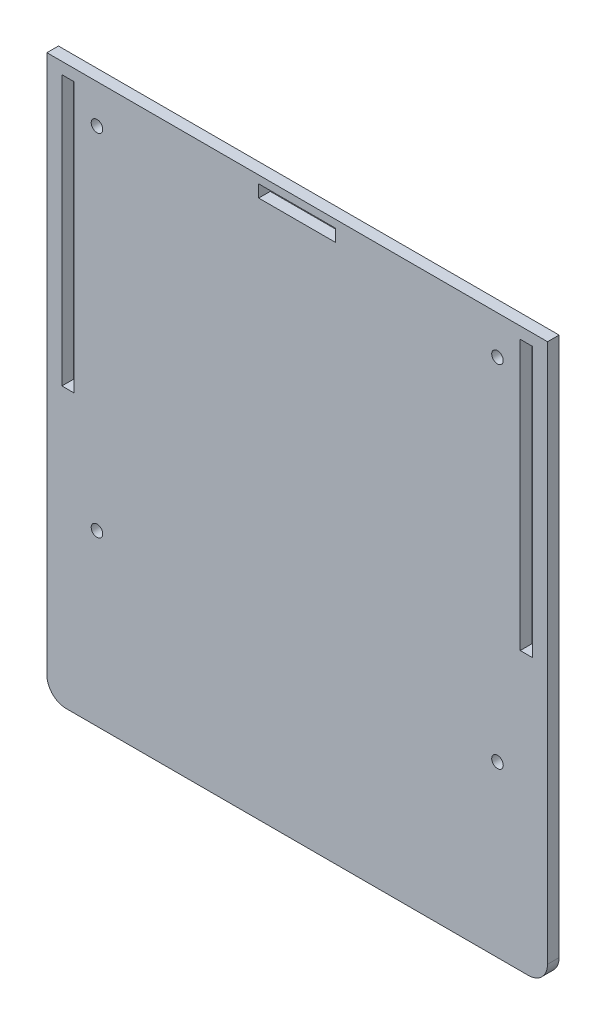
SolidWorks part; units mm, degrees
material "Maple"
ref_plane "Front Plane" through (0, 0, 0) normal (0, 0, 1) x (1, 0, 0)
ref_plane "Top Plane" through (0, 0, 0) normal (0, 1, 0) x (1, 0, 0)
ref_plane "Right Plane" through (0, 0, 0) normal (1, 0, 0) x (0, 0, -1)
sketch "Sketch1" plane through (0, 0, 0) normal (0, 0, 1) x (1, 0, 0)
  line L1 (-60, -75) -> (60, -75)
  line L5 (-65, 0) -> (65, 0) construction
  line L18 (-65, -70) -> (-65, 70)
  line L19 (-10, 68) -> (10, 68)
  line L20 (-10, 68) -> (-10, 64.8)
  line L21 (-10, 64.8) -> (10, 64.8)
  line L22 (10, 68) -> (10, 64.8)
  line L23 (-10, 68) -> (10, 64.8) construction
  line L24 (-10, 64.8) -> (10, 68) construction
  line L25 (65, 70) -> (65, -70)
  line L29 (-61.1, 67) -> (-61.1, -3)
  line L30 (-61.1, -3) -> (-57.9, -3)
  line L31 (-57.9, 67) -> (-57.9, -3)
  line L32 (-61.1, 67) -> (-57.9, -3) construction
  line L33 (-61.1, -3) -> (-57.9, 67) construction
  line L34 (-65, 32) -> (-59.5, 32) construction
  line L36 (57.9, 67) -> (57.9, -3)
  line L37 (57.9, -3) -> (61.1, -3)
  line L38 (61.1, 67) -> (61.1, -3)
  line L39 (57.9, 67) -> (61.1, -3) construction
  line L40 (57.9, -3) -> (61.1, 67) construction
  line L41 (-59.5, 32) -> (59.5, 32) construction
  line L42 (59.5, 32) -> (65, 32) construction
  line L46 (61.1, 67) -> (57.9, 67)
  line L47 (-61.1, 67) -> (-57.9, 67)
  line L48 (-65, 70) -> (65, 70)
  line L49 (-65, -31) -> (-52, -31) construction
  line L50 (-52, -31) -> (52, -31) construction
  line L51 (52, -31) -> (65, -31) construction
  arc A1 (65, -70) -> (60, -75) centre (60, -70) cw
  arc A2 (-60, -75) -> (-65, -70) centre (-60, -70) cw
  circle A3 centre (-52, -31) radius 1.5
  circle A4 centre (52, -31) radius 1.5
  circle A5 centre (52, 60) radius 1.5
  circle A6 centre (-52, 60) radius 1.5
  point P0 (0, 0)
  point P6 (-59.5, 32)
  point P12 (59.5, 32)
  point P16 (0, 66.4)
  point P22 (65, -75)
  point P31 (59.5, 67)
  point P32 (0, 0)
  point P34 (-65, -75)
  dimension "D7" = 145
  dimension "D6" = 5
  dimension "D10" = 104
  dimension "D11" = 3
  dimension "D1" = 130
  dimension "D2" = 3
  dimension "D3" = 20
  dimension "D4" = 3.2
  dimension "D5" = 5.5
  dimension "D8" = 70
  dimension "D9" = 2
  dimension "D12" = 10
  dimension "D13" = 91
extrude "Boss-Extrude1" add sketch "Sketch1" along normal blind 3
